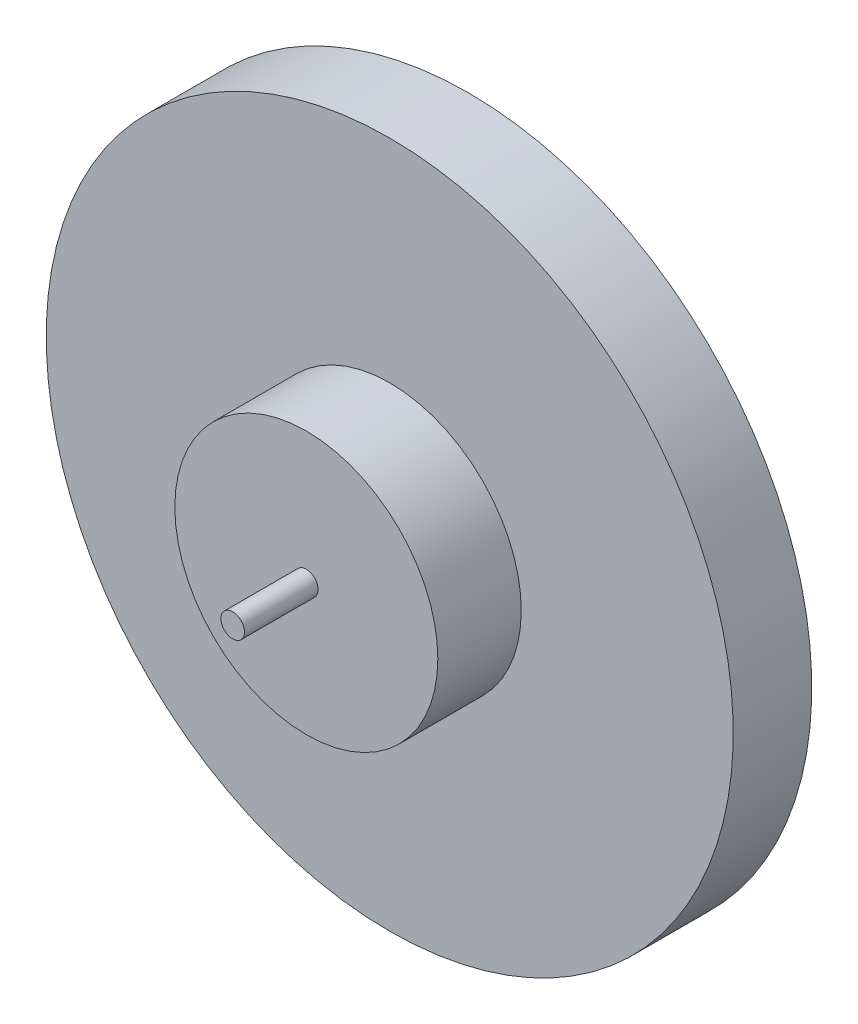
SolidWorks part; units mm, degrees
ref_plane "前视基准面" through (0, 0, 0) normal (0, 0, 1) x (1, 0, 0)
ref_plane "上视基准面" through (0, 0, 0) normal (0, 1, 0) x (1, 0, 0)
ref_plane "右视基准面" through (0, 0, 0) normal (1, 0, 0) x (0, 0, -1)
sketch "草图3" plane through (0, 0, 0) normal (1, 0, 0) x (0, 0, -1)
  line L0 (0, -4327.0198) -> (0, 212023.9691) construction
  line L1 (0, 0) -> (0, 175)
  line L2 (0, 175) -> (20, 175)
  line L3 (20, 175) -> (20, 67)
  line L4 (20, 67) -> (62.5, 67)
  line L8 (62.5, 6) -> (100, 6)
  line L9 (100, 6) -> (100, 0)
  line L10 (100, 0) -> (0, 0)
  line L11 (62.5, 67) -> (62.5, 6)
  dimension "D1" = 175
  dimension "D2" = 20
  dimension "D3" = 100
  dimension "D4" = 6
  dimension "D5" = 67
  dimension "D6" = 62.5
revolve "旋转1" add sketch "草图3" angle 360 about L10
mirror "镜向1" about plane through (0, 0, 0) normal (0, 0, 1) of "旋转1"
